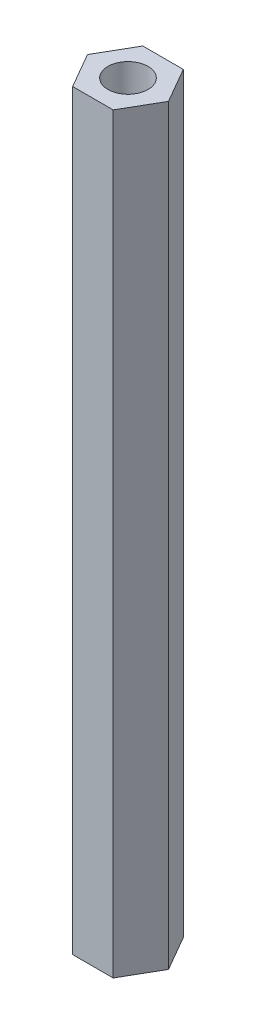
SolidWorks part; units mm, degrees
ref_plane "Front Plane" through (0, 0, 0) normal (0, 0, 1) x (1, 0, 0)
ref_plane "Top Plane" through (0, 0, 0) normal (0, 1, 0) x (1, 0, 0)
ref_plane "Right Plane" through (0, 0, 0) normal (1, 0, 0) x (0, 0, -1)
sketch "Sketch1" plane through (0, 0, 0) normal (0, 1, 0) x (1, 0, 0)
  line L1 (2.0207, 3.5) -> (-2.0207, 3.5)
  line L2 (-2.0207, 3.5) -> (-4.0415, 0)
  line L3 (-4.0415, 0) -> (-2.0207, -3.5)
  line L4 (-2.0207, -3.5) -> (2.0207, -3.5)
  line L5 (2.0207, -3.5) -> (4.0415, 0)
  line L6 (4.0415, 0) -> (2.0207, 3.5)
  circle A0 centre (0, 0) radius 3.5 construction
  circle A1 centre (0, 0) radius 2
  dimension "D1" = 4
  dimension "D2" = 7
extrude "Boss-Extrude1" add sketch "Sketch1" along normal blind 75
